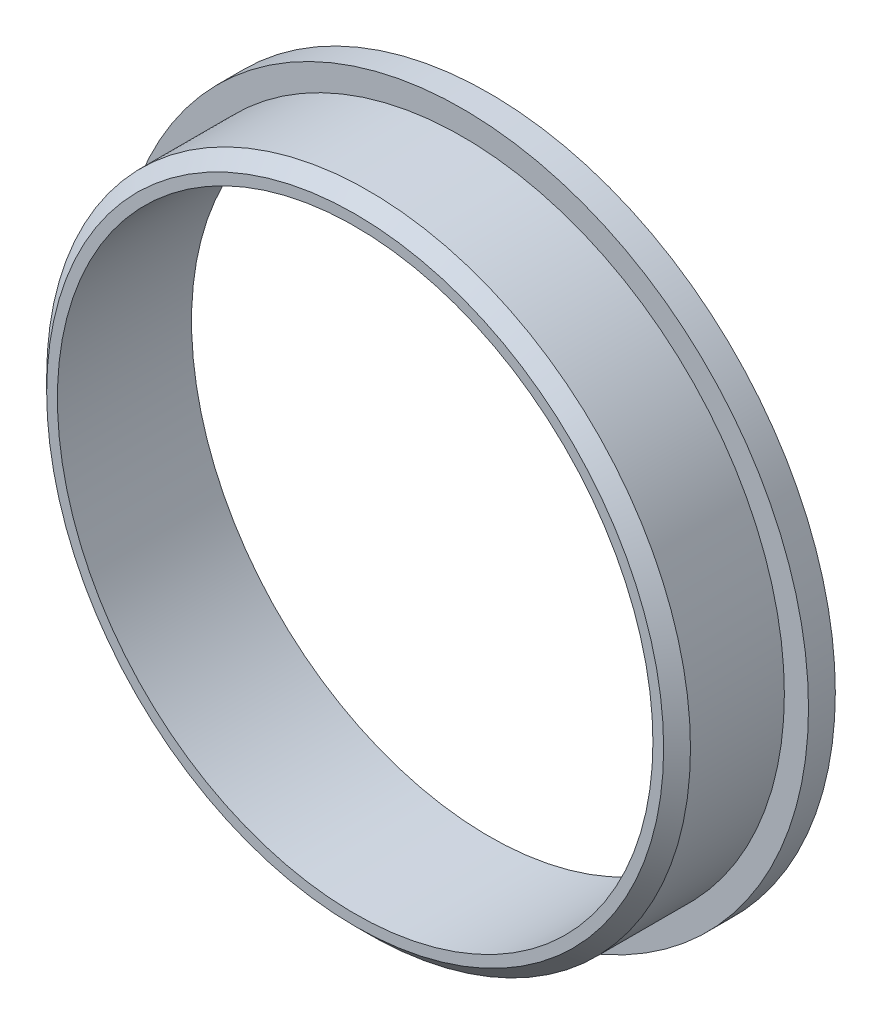
SolidWorks part; units mm, degrees
material "POM 乙缩醛共聚物"
ref_plane "前视基准面" through (0, 0, 0) normal (0, 0, 1) x (1, 0, 0)
ref_plane "上视基准面" through (0, 0, 0) normal (0, 1, 0) x (1, 0, 0)
ref_plane "右视基准面" through (0, 0, 0) normal (1, 0, 0) x (0, 0, -1)
sketch "草图1" plane through (0, 0, 0) normal (0, 0, 1) x (1, 0, 0)
  line L0 (0, 0) -> (0, 117.0916) construction
  circle A0 centre (0, 0) radius 11.1
  circle A1 centre (0, 0) radius 12.9
  dimension "D1" = 22.2
  dimension "D2" = 25.8
extrude "凸台-拉伸1" add sketch "草图1" along normal blind 5
sketch "草图3" plane through (0, 0, 5) normal (0, 0, 1) x (1, 0, 0)
  circle A0 centre (0, 0) radius 12
  circle A1 centre (0, 0) radius 16.6628
  dimension "D1" = 24
extrude "切除-拉伸1" cut sketch "草图3" against normal offset from surface (4 mm away) 1 up to face at (12.9, 0, 0)
chamfer "倒角1" distance 0.5 angle 45 1 edges at (12, 0, 5)
equation "\"A\"= \"代号代码\""
equation "\"B\"= \"名称代码\""
